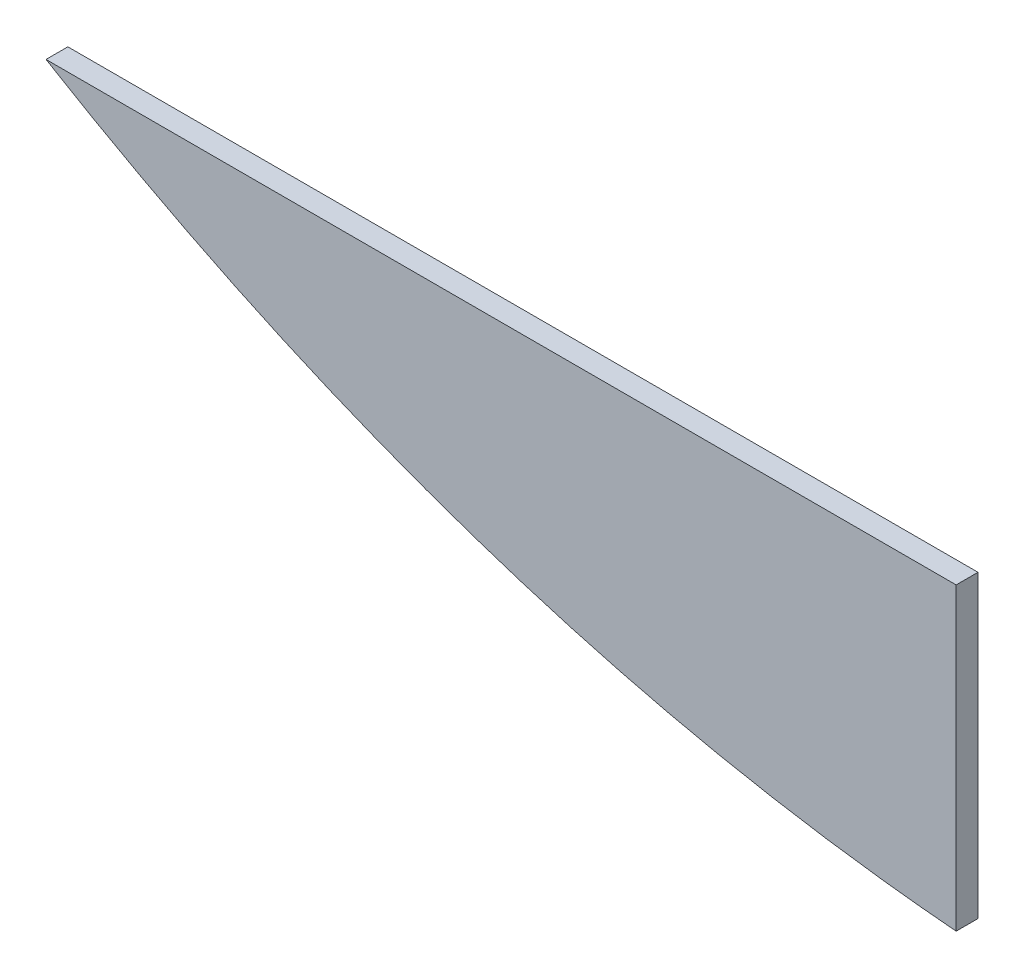
SolidWorks part; units mm, degrees
ref_plane "Front Plane" through (0, 0, 0) normal (0, 0, 1) x (1, 0, 0)
ref_plane "Top Plane" through (0, 0, 0) normal (0, 1, 0) x (1, 0, 0)
ref_plane "Right Plane" through (0, 0, 0) normal (1, 0, 0) x (0, 0, -1)
sketch "Sketch1" plane through (0, 0, 0) normal (0, 0, 1) x (1, 0, 0)
  line L0 (66.1131, -21.7851) -> (66.1131, 21.7851)
  line L1 (-66.1131, 21.7851) -> (66.1131, 21.7851)
  spline S0 degree 3 poles (-66.1131, 21.7851) (-24.2029, -3.3402) (19.8725, -17.8637) (66.1131, -21.7851) knots 0 0 0 0 1 1 1 1
extrude "Boss-Extrude1" add sketch "Sketch1" along normal blind 3.175
